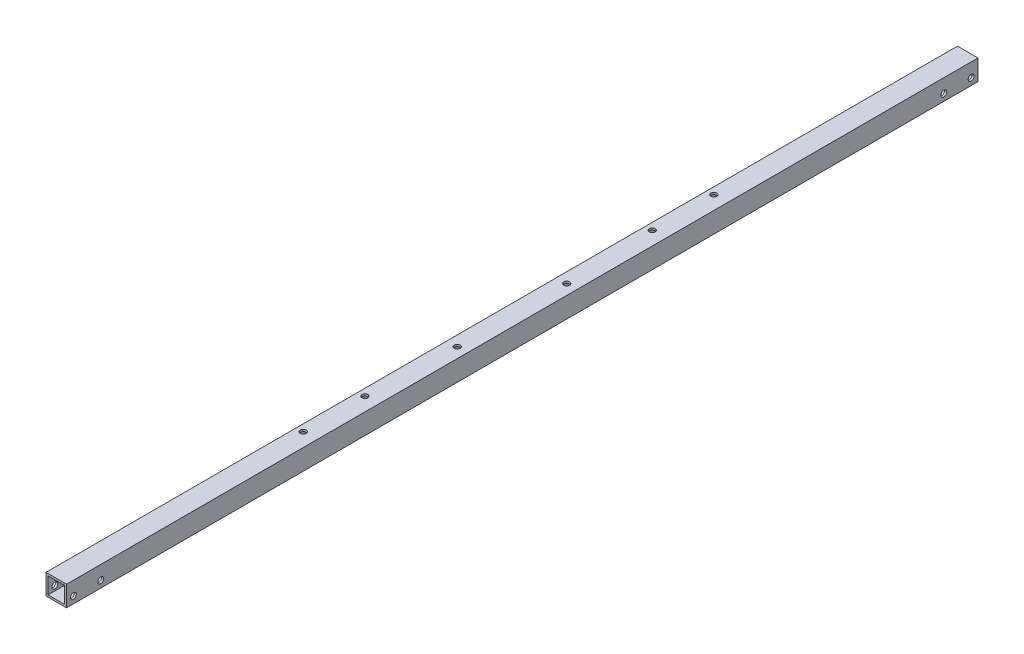
SolidWorks part; units mm, degrees
material "5052-H34"
ref_plane "正面" through (0, 0, 0) normal (0, 0, 1) x (1, 0, 0)
ref_plane "平面" through (0, 0, 0) normal (0, 1, 0) x (1, 0, 0)
ref_plane "右側面" through (0, 0, 0) normal (1, 0, 0) x (0, 0, -1)
sketch "ｽｹｯﾁ1" plane through (0, 0, 0) normal (0, 0, 1) x (1, 0, 0)
  line L1 (-7.5, 7.5) -> (7.5, 7.5)
  line L2 (-7.5, 7.5) -> (-7.5, -7.5)
  line L3 (-7.5, -7.5) -> (7.5, -7.5)
  line L4 (7.5, 7.5) -> (7.5, -7.5)
  line L5 (-7.5, 7.5) -> (7.5, -7.5) construction
  line L6 (-7.5, -7.5) -> (7.5, 7.5) construction
  point P0 (0, 0)
  dimension "D1" = 15
  dimension "D2" = 15
extrude "押し出し-薄板1" add sketch "ｽｹｯﾁ1" along normal blind 666 thin
sketch "ｽｹｯﾁ2" plane through (7.5, 0, 0) normal (1, 0, 0) x (0, 0, -1)
  line L0 (-333, 7.5) -> (-333, -7.5) construction
  line L1 (-666, 7.5) -> (0, 7.5) construction
  line L2 (-666, -7.5) -> (0, -7.5) construction
  line L3 (-333, 0) -> (-313, 0) construction
  line L4 (0, -2.5) -> (-648, -2.5) construction
  line L6 (0, -7.5) -> (0, 7.5) construction
  circle A0 centre (-333, 0) radius 2.15 construction
  circle A1 centre (-313, 0) radius 2.15 construction
  circle A2 centre (-353, 0) radius 2.15 construction
  circle A3 centre (-5, -2.5) radius 2.15
  circle A6 centre (-661, -2.5) radius 2.15
  circle A7 centre (-205, -2.5) radius 2.15 construction
  circle A8 centre (-461, -2.5) radius 2.15 construction
  circle A9 centre (-25, -2.5) radius 2.15
  circle A10 centre (-641, -2.5) radius 2.15
  dimension "D1" = 4.3
  dimension "D3" = 4.3
  dimension "D4" = 5
  dimension "D2" = 40
  dimension "D5" = 200
  dimension "D6" = 20
  dimension "D7" = 5
extrude "ｶｯﾄ - 押し出し1" cut sketch "ｽｹｯﾁ2" against normal through all
sketch "ｽｹｯﾁ3" plane through (0, 7.5, 0) normal (0, 1, 0) x (1, 0, 0)
  line L0 (-7.5, -333) -> (7.5, -333) construction
  line L1 (-7.5, -666) -> (-7.5, 0) construction
  line L2 (7.5, -666) -> (7.5, 0) construction
  line L3 (7.5, -333) -> (-7.5, -333) construction
  line L4 (-2.5, -183) -> (-2.5, -228) construction
  line L5 (0, -333) -> (0, -666) construction
  line L6 (7.5, -666) -> (-7.5, -666) construction
  circle A9 centre (-2.5, -228) radius 2.15
  circle A10 centre (-2.5, -438) radius 2.15
  circle A11 centre (-2.5, -183) radius 2.15
  circle A12 centre (-2.5, -483) radius 2.15
  circle A13 centre (0, -373) radius 2.15
  circle A14 centre (0, -293) radius 2.15
  point P21 (7.5, -333)
  dimension "D1" = 4.3
  dimension "D5" = 80
  dimension "D4" = 5
  dimension "D2" = 210
  dimension "D3" = 300
extrude "ｶｯﾄ - 押し出し2" cut sketch "ｽｹｯﾁ3" against normal through all
